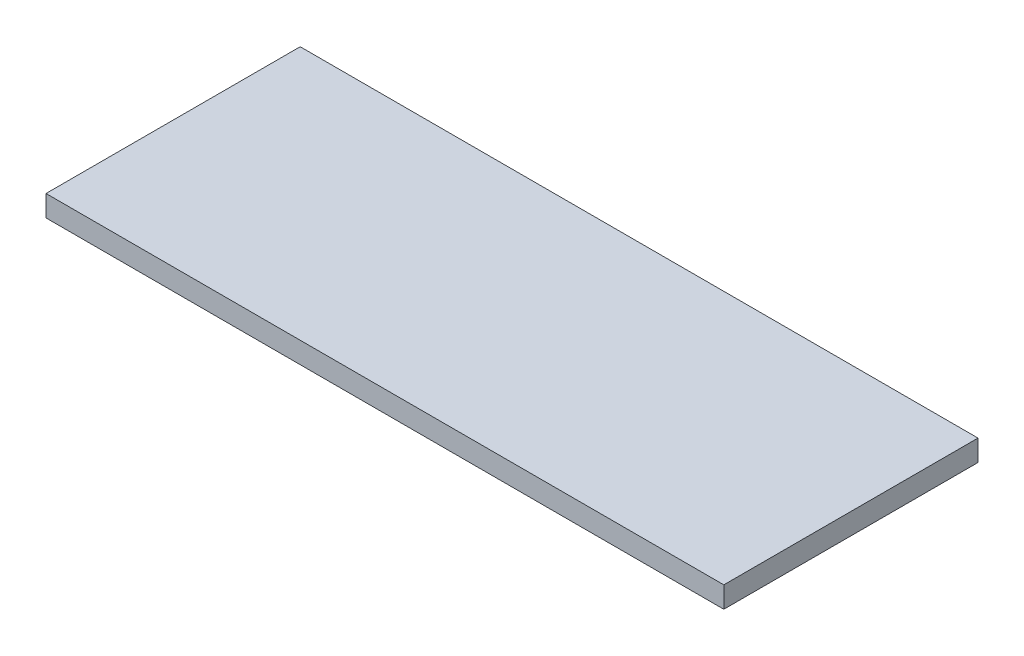
SolidWorks part; units mm, degrees
ref_plane "Front Plane" through (0, 0, 0) normal (0, 0, 1) x (1, 0, 0)
ref_plane "Top Plane" through (0, 0, 0) normal (0, 1, 0) x (1, 0, 0)
ref_plane "Right Plane" through (0, 0, 0) normal (1, 0, 0) x (0, 0, -1)
sketch "Sketch1" plane through (0, 0, 0) normal (0, 1, 0) x (1, 0, 0)
  line L1 (0, 0) -> (609.6, 0)
  line L2 (0, 0) -> (0, 228.6)
  line L3 (0, 228.6) -> (609.6, 228.6)
  line L4 (609.6, 0) -> (609.6, 228.6)
  dimension "D1" = 609.6
  dimension "D2" = 228.6
extrude "Boss-Extrude1" add sketch "Sketch1" along normal blind 19.05
